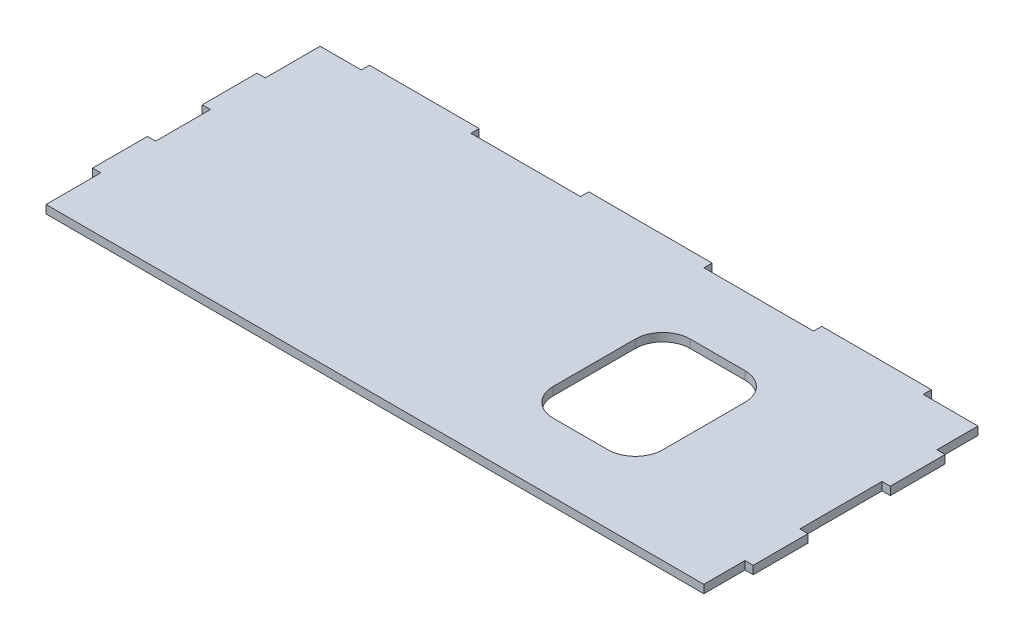
SolidWorks part; units mm, degrees
ref_plane "Front Plane" through (0, 0, 0) normal (0, 0, 1) x (1, 0, 0)
ref_plane "Top Plane" through (0, 0, 0) normal (0, 1, 0) x (1, 0, 0)
ref_plane "Right Plane" through (0, 0, 0) normal (1, 0, 0) x (0, 0, -1)
sketch "Sketch1" plane through (0, 0, 0) normal (0, 1, 0) x (1, 0, 0)
  line L0 (-118.5, -30) -> (-118.5, -50)
  line L1 (-118.5, 50) -> (121.5, 50)
  line L2 (-118.5, 50) -> (-118.5, 30)
  line L3 (-118.5, -50) -> (121.5, -50)
  line L4 (121.5, 50) -> (121.5, 35)
  line L5 (-118.5, -30) -> (-121.5, -30)
  line L7 (-118.5, -10) -> (-121.5, -10)
  line L8 (-121.5, -30) -> (-121.5, -10)
  line L9 (-118.5, 10) -> (-118.5, -10)
  line L10 (-118.5, 30) -> (-121.5, 30)
  line L12 (-118.5, 10) -> (-121.5, 10)
  line L13 (-121.5, 30) -> (-121.5, 10)
  line L14 (121.5, 15) -> (121.5, -15)
  line L15 (121.5, 35) -> (124.5, 35)
  line L17 (121.5, 15) -> (124.5, 15)
  line L18 (124.5, 35) -> (124.5, 15)
  line L19 (121.5, -35) -> (124.5, -35)
  line L21 (121.5, -15) -> (124.5, -15)
  line L22 (124.5, -35) -> (124.5, -15)
  line L23 (121.5, -35) -> (121.5, -50)
  dimension "D1" = 100
  dimension "D2" = 240
  dimension "D3" = 50
  dimension "D4" = 121.5
  dimension "D5" = 3
  dimension "D6" = 20
  dimension "D7" = 20
  dimension "D8" = 20
  dimension "D9" = 20
  dimension "D10" = 3
  dimension "D11" = 20
  dimension "D12" = 20
  dimension "D13" = 15
  dimension "D14" = 15
  dimension "D15" = 3
  dimension "D16" = 3
extrude "Boss-Extrude1" add sketch "Sketch1" along normal blind 3
sketch "Sketch2" plane through (0, 0, -50) normal (0, 0, -1) x (-1, 0, 0)
  line L0 (-121.5, 3) -> (118.5, 3) construction
  line L1 (-101.5, 3) -> (-61.5, 3)
  line L2 (-101.5, 3) -> (-101.5, 0)
  line L3 (-101.5, 0) -> (-61.5, 0)
  line L4 (-61.5, 3) -> (-61.5, 0)
  line L5 (-121.5, 0) -> (118.5, 0) construction
  line L6 (-121.5, 3) -> (-121.5, 0) construction
  line L7 (-21.5, 3) -> (23.5, 3)
  line L8 (-21.5, 3) -> (-21.5, 0)
  line L9 (-21.5, 0) -> (23.5, 0)
  line L10 (23.5, 3) -> (23.5, 0)
  line L11 (63.5, 3) -> (103.5, 3)
  line L12 (63.5, 3) -> (63.5, 0)
  line L13 (63.5, 0) -> (103.5, 0)
  line L14 (103.5, 3) -> (103.5, 0)
  line L15 (118.5, 3) -> (118.5, 0) construction
  dimension "D1" = 40
  dimension "D2" = 20
  dimension "D3" = 45
  dimension "D4" = 40
  dimension "D5" = 40
  dimension "D6" = 15
extrude "Boss-Extrude2" add sketch "Sketch2" along normal blind 3
sketch "Sketch3" plane through (0, 3, 0) normal (0, 1, 0) x (1, 0, 0)
  line L0 (121.5, -15) -> (121.5, 15) construction
  line L1 (41.5, 25) -> (61.5, 25)
  line L2 (31.5, 15) -> (31.5, -15)
  line L3 (41.5, -25) -> (61.5, -25)
  line L4 (71.5, 15) -> (71.5, -15)
  line L5 (61.5, 50) -> (21.5, 50) construction
  arc A0 (31.5, -15) -> (41.5, -25) centre (41.5, -15) ccw
  arc A1 (61.5, -25) -> (71.5, -15) centre (61.5, -15) ccw
  arc A2 (61.5, 25) -> (71.5, 15) centre (61.5, 15) cw
  arc A3 (41.5, 25) -> (31.5, 15) centre (41.5, 15) ccw
  point P10 (31.5, -25)
  point P13 (71.5, -25)
  point P18 (31.5, 25)
  dimension "D5" = 10
  dimension "D1" = 50
  dimension "D2" = 40
  dimension "D3" = 50
  dimension "D4" = 25
extrude "Cut-Extrude1" cut sketch "Sketch3" against normal blind 3
